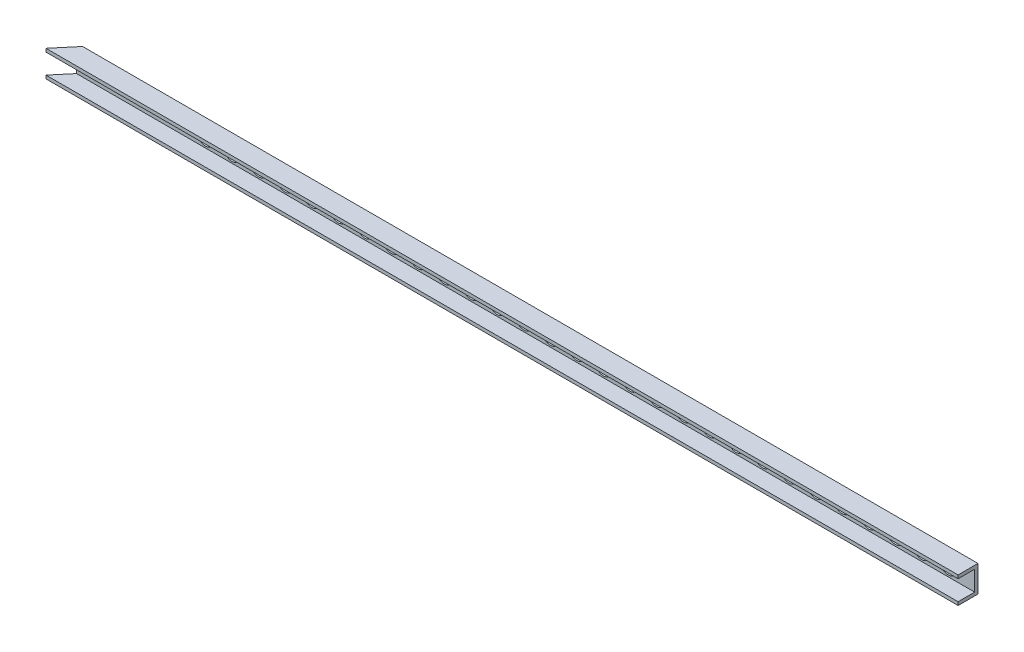
SolidWorks part; units mm, degrees
material "Plain Carbon Steel"
ref_plane "Front Plane" through (0, 0, 0) normal (0, 0, 1) x (1, 0, 0)
ref_plane "Top Plane" through (0, 0, 0) normal (0, 1, 0) x (1, 0, 0)
ref_plane "Right Plane" through (0, 0, 0) normal (1, 0, 0) x (0, 0, -1)
sketch "Sketch1" plane through (0, 0, 0) normal (1, 0, 0) x (0, 0, -1)
  line L0 (4.7625, 4.7625) -> (-4.7625, 4.7625)
  line L1 (6.35, 6.35) -> (-6.35, 6.35)
  line L2 (6.35, 6.35) -> (6.35, -6.35)
  line L3 (6.35, -6.35) -> (-6.35, -6.35)
  line L4 (-6.35, 6.35) -> (-6.35, -6.35)
  line L5 (6.35, 6.35) -> (-6.35, -6.35) construction
  line L6 (6.35, -6.35) -> (-6.35, 6.35) construction
  line L7 (-4.7625, 4.7625) -> (-4.7625, -4.7625)
  line L8 (4.7625, -4.7625) -> (-4.7625, -4.7625)
  line L9 (4.7625, 4.7625) -> (4.7625, -4.7625)
  dimension "D1" = 12.7
  dimension "D2" = 12.7
  dimension "D3" = 1.5875
extrude "Boss-Extrude1" add sketch "Sketch1" against normal blind 185.42 and the other way blind 254
sketch "Sketch2" plane through (0, 0, 0) normal (0, 1, 0) x (1, 0, 0)
  line L0 (-185.42, -6.35) -> (-135.9836, 52.566) construction
  line L1 (-185.42, -6.35) -> (-174.2505, 6.9613)
  line L2 (-185.42, -6.35) -> (-194.2478, 1.0574)
  line L3 (-174.2505, 6.9613) -> (-183.0782, 14.3687)
  line L4 (-194.2478, 1.0574) -> (-183.0782, 14.3687)
extrude "Cut-Extrude1" cut sketch "Sketch2" against normal through all and the other way through all
sketch "Sketch3" [suppressed] plane through (0, 6.35, 0) normal (0, 1, 0) x (1, 0, 0)
  line L0 (190.5, 0) -> (152.4, 0) construction
  line L1 (190.5, -3.175) -> (152.4, -3.175)
  line L2 (190.5, 3.175) -> (152.4, 3.175)
  line L3 (139.7, 0) -> (101.6, 0) construction
  line L4 (139.7, -3.175) -> (101.6, -3.175)
  line L5 (139.7, 3.175) -> (101.6, 3.175)
  line L6 (88.9, 0) -> (50.8, 0) construction
  line L7 (88.9, -3.175) -> (50.8, -3.175)
  line L8 (88.9, 3.175) -> (50.8, 3.175)
  line L9 (38.1, 0) -> (0, 0) construction
  line L10 (38.1, -3.175) -> (0, -3.175)
  line L11 (38.1, 3.175) -> (0, 3.175)
  line L12 (-12.7, 0) -> (-50.8, 0) construction
  line L13 (-12.7, -3.175) -> (-50.8, -3.175)
  line L14 (-12.7, 3.175) -> (-50.8, 3.175)
  line L15 (-63.5, 0) -> (-101.6, 0) construction
  line L16 (-63.5, -3.175) -> (-101.6, -3.175)
  line L17 (-63.5, 3.175) -> (-101.6, 3.175)
  line L19 (203.2, 0) -> (241.3, 0) construction
  line L20 (203.2, 3.175) -> (241.3, 3.175)
  line L21 (203.2, -3.175) -> (241.3, -3.175)
  line L22 (254, 6.35) -> (254, -6.35) construction
  arc A0 (190.5, -3.175) -> (190.5, 3.175) centre (190.5, 0) ccw
  arc A1 (152.4, 3.175) -> (152.4, -3.175) centre (152.4, 0) ccw
  arc A2 (139.7, -3.175) -> (139.7, 3.175) centre (139.7, 0) ccw
  arc A3 (101.6, 3.175) -> (101.6, -3.175) centre (101.6, 0) ccw
  arc A4 (88.9, -3.175) -> (88.9, 3.175) centre (88.9, 0) ccw
  arc A5 (50.8, 3.175) -> (50.8, -3.175) centre (50.8, 0) ccw
  arc A6 (38.1, -3.175) -> (38.1, 3.175) centre (38.1, 0) ccw
  arc A7 (0, 3.175) -> (0, -3.175) centre (0, 0) ccw
  arc A8 (-12.7, -3.175) -> (-12.7, 3.175) centre (-12.7, 0) ccw
  arc A9 (-50.8, 3.175) -> (-50.8, -3.175) centre (-50.8, 0) ccw
  arc A10 (203.2, 3.175) -> (203.2, -3.175) centre (203.2, 0) ccw
  arc A11 (241.3, -3.175) -> (241.3, 3.175) centre (241.3, 0) ccw
  arc A12 (-63.5, -3.175) -> (-63.5, 3.175) centre (-63.5, 0) ccw
  arc A13 (-101.6, 3.175) -> (-101.6, -3.175) centre (-101.6, 0) ccw
  point P3 (171.45, 0)
  point P8 (120.65, 0)
  point P15 (69.85, 0)
  point P22 (19.05, 0)
  point P29 (-31.75, 0)
  point P38 (222.25, 0)
  point P45 (-82.55, 0)
  dimension "D2" = 38.1
  dimension "D3" = 6.35
  dimension "D4" = 12.7
  dimension "D5" = 12.7
  dimension "D6" = 12.7
  dimension "D7" = 12.7
  dimension "D8" = 12.7
  dimension "D9" = 12.7
  dimension "D18" = 12.7
sketch "Sketch4" plane through (0, 0, 6.35) normal (0, 0, 1) x (1, 0, 0)
  line L0 (241.3, 0) -> (228.6, 0) construction
  line L18 (254, 6.35) -> (254, -6.35) construction
  circle A0 centre (241.3, 0) radius 3.9688
  circle A1 centre (228.6, 0) radius 3.9688
  circle A2 centre (215.9, 0) radius 3.9688
  circle A3 centre (203.2, 0) radius 3.9688
  circle A4 centre (190.5, 0) radius 3.9688
  circle A5 centre (177.8, 0) radius 3.9688
  circle A6 centre (165.1, 0) radius 3.9688
  circle A7 centre (152.4, 0) radius 3.9688
  circle A8 centre (139.7, 0) radius 3.9688
  circle A9 centre (127, 0) radius 3.9688
  circle A10 centre (114.3, 0) radius 3.9688
  circle A11 centre (101.6, 0) radius 3.9688
  circle A12 centre (88.9, 0) radius 3.9688
  circle A13 centre (76.2, 0) radius 3.9688
  circle A14 centre (63.5, 0) radius 3.9688
  circle A15 centre (50.8, 0) radius 3.9688
  circle A16 centre (38.1, 0) radius 3.9688
  circle A17 centre (25.4, 0) radius 3.9688
  circle A18 centre (12.7, 0) radius 3.9688
  circle A19 centre (0, 0) radius 3.9688
  circle A20 centre (-12.7, 0) radius 3.9688
  circle A21 centre (-25.4, 0) radius 3.9688
  circle A22 centre (-38.1, 0) radius 3.9688
  circle A23 centre (-50.8, 0) radius 3.9688
  circle A24 centre (-63.5, 0) radius 3.9688
  circle A25 centre (-76.2, 0) radius 3.9688
  circle A26 centre (-88.9, 0) radius 3.9688
  circle A27 centre (-101.6, 0) radius 3.9688
  circle A28 centre (-114.3, 0) radius 3.9688
  point P43 (254, 0)
  dimension "D1" = 7.9375
  dimension "D2" = 12.7
  dimension "D3" = 29
  dimension "D4" = 12.7
extrude "Cut-Extrude3" cut sketch "Sketch4" against normal through all
sketch "Sketch5" plane through (254, 0, 0) normal (1, 0, 0) x (0, 0, -1)
  line L0 (-6.35, 6.35) -> (-6.35, -6.35) construction
  line L1 (-6.35, 6.985) -> (-3.175, 6.985)
  line L2 (-6.35, 6.985) -> (-6.35, -6.985)
  line L3 (-6.35, -6.985) -> (-3.175, -6.985)
  line L4 (-3.175, 6.985) -> (-3.175, -6.985)
  point P4 (-3.175, 0)
  dimension "D1" = 13.97
  dimension "D2" = 3.175
extrude "Cut-Extrude4" cut sketch "Sketch5" against normal through all
